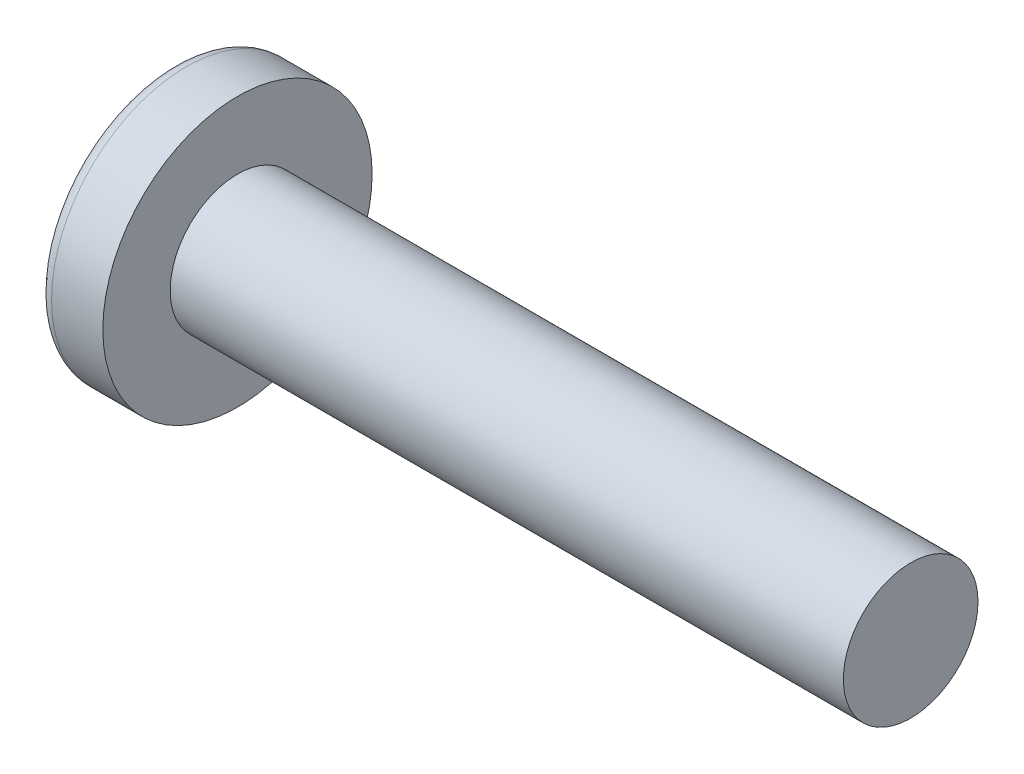
SolidWorks part; units mm, degrees
ref_plane "前视基准面" through (0, 0, 0) normal (0, 0, 1) x (1, 0, 0)
ref_plane "上视基准面" through (0, 0, 0) normal (0, 1, 0) x (1, 0, 0)
ref_plane "右视基准面" through (0, 0, 0) normal (1, 0, 0) x (0, 0, -1)
other "Configuration Table"
sketch "草图1" plane through (0, 0, 0) normal (0, 0, 1) x (1, 0, 0)
  line L0 (0, 0) -> (-24.6481, 0) construction
  line L1 (0, 0) -> (0, 2)
  line L2 (0, 2) -> (-20, 2)
  line L3 (-20, 2) -> (-20, 4)
  line L4 (-20, 4) -> (-21.5244, 4)
  line L5 (0, 0) -> (-23.1, 0)
  arc A0 (-21.5244, 4) -> (-21.8473, 3.8361) centre (-21.5244, 3.6) ccw
  arc A1 (-21.8473, 3.8361) -> (-23.1, 0) centre (-16.6, 0) ccw
  point P11 (0, 0)
  dimension "D3" = 0.4
  dimension "D6" = 6.5
  dimension "D1" = 4
  dimension "D2" = 20
  dimension "D4" = 8
  dimension "D5" = 3.1
revolve "旋转1" add sketch "草图1" angle 360 about L0
cosmetic thread "装饰螺纹线1" parameters "D1"=18.6, "D2"=3
sketch "草图3" plane through (0, 0, 0) normal (0, 0, 1) x (1, 0, 0)
  line L0 (-20.8, -1) -> (-23.8, -2.4957)
  line L1 (-23.8, -2.4957) -> (-23.8, 2.4957)
  line L7 (-20.8, 1) -> (-23.8, 2.4957)
  line L8 (-20.8, 1) -> (-20.8, -1)
  line L9 (-20, -4) -> (-20, 4) construction
  point P2 (-20.8, 0)
  point P8 (-23.8, 0)
  dimension "D1" = 53
  dimension "D2" = 2
  dimension "D3" = 0.8
  dimension "D4" = 3
extrude "切除-拉伸2" cut sketch "草图3" against normal mid plane 1
pattern_circular "阵列(圆周)1" count 2 every 90 about axis through (0, 0, 0) along (1, 0, 0) of "切除-拉伸2"
sketch "草图4" plane through (-20.8, 0, 0) normal (-1, 0, 0) x (0, 0, 1)
  circle A0 centre (0, 0) radius 0.85
  dimension "D1" = 1.7
extrude "切除-拉伸3" cut sketch "草图4" along normal up to vertex up to point (-23.0614, -0.5, -0.5)
